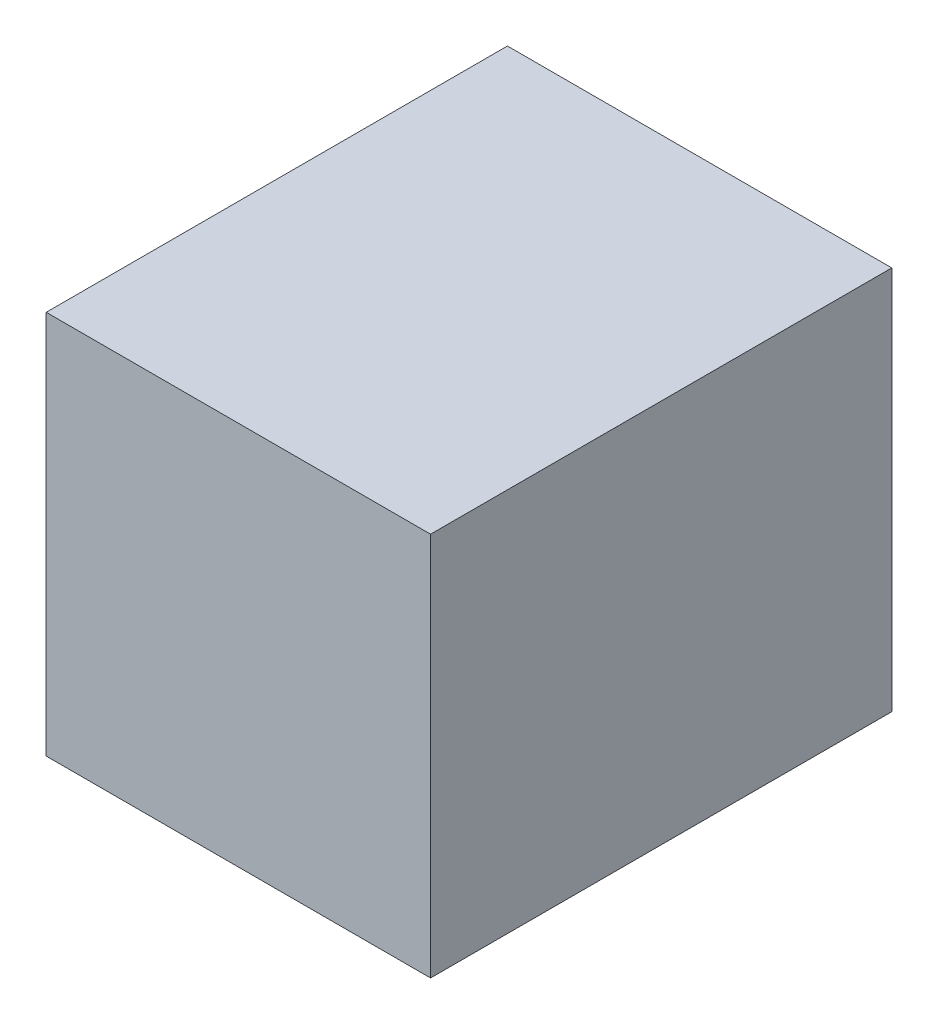
SolidWorks part; units mm, degrees
material "Polyethylene Cross-Linked"
ref_plane "Front Plane" through (0, 0, 0) normal (0, 0, 1) x (1, 0, 0)
ref_plane "Top Plane" through (0, 0, 0) normal (0, 1, 0) x (1, 0, 0)
ref_plane "Right Plane" through (0, 0, 0) normal (1, 0, 0) x (0, 0, -1)
sketch "Sketch1" plane through (0, 0, 0) normal (0, 1, 0) x (1, 0, 0)
  line L1 (-254, 304.8) -> (254, 304.8)
  line L2 (-254, 304.8) -> (-254, -304.8)
  line L3 (-254, -304.8) -> (254, -304.8)
  line L4 (254, 304.8) -> (254, -304.8)
  line L5 (-254, 304.8) -> (254, -304.8) construction
  line L6 (-254, -304.8) -> (254, 304.8) construction
  point P0 (0, 0)
  dimension "D1" = 508
  dimension "D2" = 609.6
extrude "Boss-Extrude1" add sketch "Sketch1" along normal blind 508
